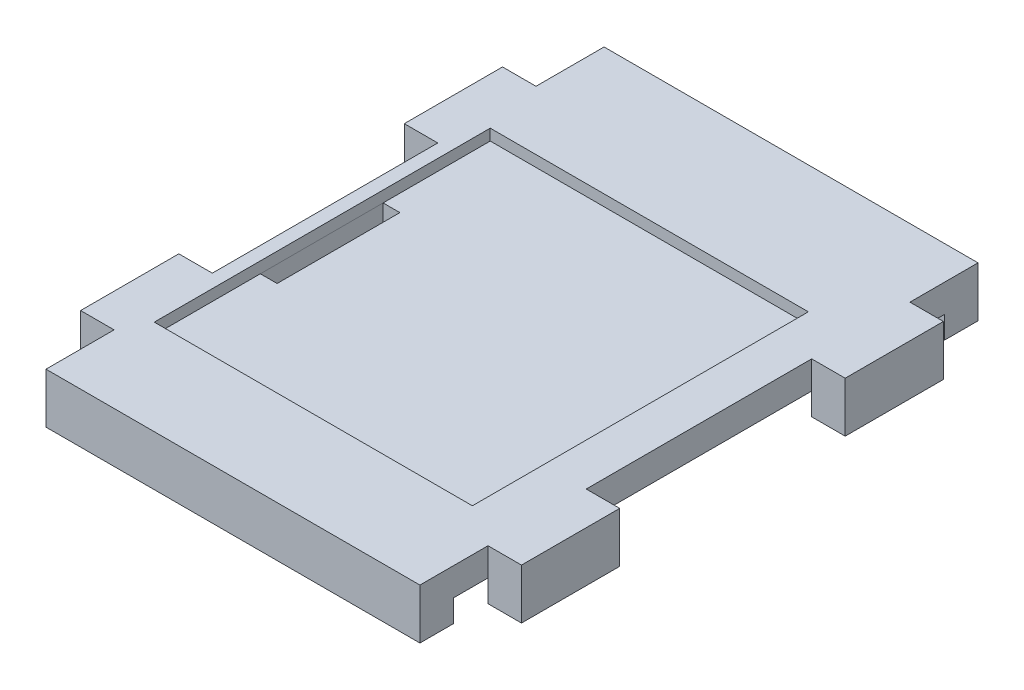
SolidWorks part; units mm, degrees
ref_plane "Front Plane" through (0, 0, 0) normal (0, 0, 1) x (1, 0, 0)
ref_plane "Top Plane" through (0, 0, 0) normal (0, 1, 0) x (1, 0, 0)
ref_plane "Right Plane" through (0, 0, 0) normal (1, 0, 0) x (0, 0, -1)
sketch "Sketch3" plane through (0, 0, 0) normal (0, 1, 0) x (1, 0, 0)
  line L1 (0, 0) -> (39.5, 0)
  line L2 (0, 0) -> (0, 50)
  line L3 (0, 50) -> (39.5, 50)
  line L4 (39.5, 0) -> (39.5, 50)
  line L5 (3, 3) -> (36.5, 3)
  line L6 (3, 3) -> (3, 47)
  line L7 (3, 47) -> (36.5, 47)
  line L8 (36.5, 3) -> (36.5, 47)
  dimension "D1" = 50
  dimension "D2" = 39.5
  dimension "D3" = 3
  dimension "D4" = 3
  dimension "D5" = 33.5
  dimension "D6" = 44
extrude "Boss-Extrude1" add sketch "Sketch3" along normal blind 2
sketch "Sketch4" plane through (0, 2, 0) normal (0, 1, 0) x (1, 0, 0)
  line L1 (0, 0) -> (39.5, 0)
  line L2 (0, 0) -> (0, 50)
  line L3 (0, 50) -> (39.5, 50)
  line L4 (39.5, 0) -> (39.5, 50)
extrude "Boss-Extrude2" add sketch "Sketch4" along normal blind 1.5
sketch "Sketch5" plane through (0, 3.5, 0) normal (0, 1, 0) x (1, 0, 0)
  line L0 (0, 50) -> (0, 0) construction
  line L1 (4.206, 29) -> (5.706, 29)
  line L2 (4.206, 29) -> (4.206, 18)
  line L3 (4.206, 18) -> (5.706, 18)
  line L4 (5.706, 29) -> (5.706, 18)
  line L5 (0, 0) -> (39.5, 0) construction
  dimension "D1" = 4.206
  dimension "D2" = 18
  dimension "D3" = 11
  dimension "D4" = 1.5
extrude "Cut-Extrude1" cut sketch "Sketch5" against normal blind 3
sketch "Sketch7" plane through (0, 3.5, 0) normal (0, 1, 0) x (1, 0, 0)
  line L0 (39.5, 0) -> (39.5, 50) construction
  line L1 (0, 50) -> (39.5, 50)
  line L2 (0, 50) -> (0, 0)
  line L3 (0, 0) -> (39.5, 0)
  line L4 (39.5, 50) -> (39.5, 0)
  line L6 (4.2, 38.6) -> (32.7, 38.6)
  line L7 (4.2, 38.6) -> (4.2, 8.5)
  line L8 (4.2, 8.5) -> (32.7, 8.5)
  line L9 (32.7, 38.6) -> (32.7, 8.5)
  dimension "D1" = 28.5
  dimension "D2" = 30.1
  dimension "D3" = 11.4
  dimension "D4" = 4.2
extrude "Boss-Extrude3" add sketch "Sketch7" along normal blind 1
sketch "Sketch8" plane through (0, 0, 0) normal (0, -1, 0) x (1, 0, 0)
  line L0 (3, -47) -> (3, -3) construction
  line L1 (0, 0) -> (3, 0)
  line L2 (0, 0) -> (0, -6.1)
  line L3 (0, -6.1) -> (3, -6.1)
  line L4 (3, 0) -> (3, -6.1)
  line L5 (0, -50) -> (0, 0) construction
  line L6 (0, -14.9) -> (3, -14.9)
  line L7 (0, -14.9) -> (0, -35.1)
  line L8 (0, -35.1) -> (3, -35.1)
  line L9 (3, -14.9) -> (3, -35.1)
  line L10 (36.5, -3) -> (36.5, -47) construction
  line L11 (0, -50) -> (3, -50)
  line L12 (0, -50) -> (0, -43.9)
  line L13 (0, -43.9) -> (3, -43.9)
  line L14 (3, -50) -> (3, -43.9)
  line L15 (39.5, 0) -> (36.5, 0)
  line L16 (39.5, 0) -> (39.5, -6.1)
  line L17 (39.5, -6.1) -> (36.5, -6.1)
  line L18 (36.5, 0) -> (36.5, -6.1)
  line L19 (39.5, 0) -> (39.5, -50) construction
  line L20 (39.5, -14.9) -> (36.5, -14.9)
  line L21 (39.5, -14.9) -> (39.5, -35.1)
  line L22 (39.5, -35.1) -> (36.5, -35.1)
  line L23 (36.5, -14.9) -> (36.5, -35.1)
  line L24 (39.5, -50) -> (0, -50) construction
  line L25 (39.5, -50) -> (36.5, -50)
  line L26 (39.5, -50) -> (39.5, -43.9)
  line L27 (39.5, -43.9) -> (36.5, -43.9)
  line L28 (36.5, -50) -> (36.5, -43.9)
  dimension "D1" = 6.1
  dimension "D2" = 20.2
  dimension "D3" = 6.1
  dimension "D4" = 8.8
extrude "Cut-Extrude2" cut sketch "Sketch8" against normal blind 4.5
